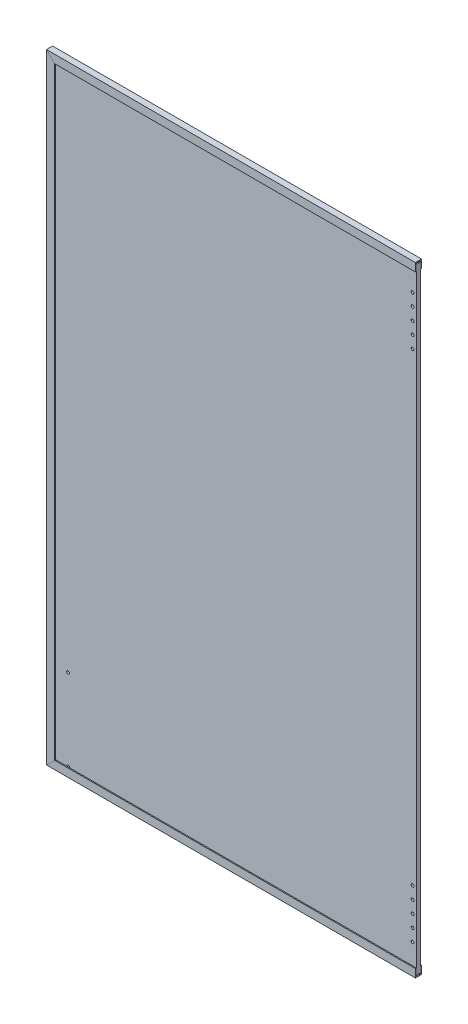
SolidWorks part; units mm, degrees
material "PC High Viscosity"
ref_plane "Front Plane" through (0, 0, 0) normal (0, 0, 1) x (1, 0, 0)
ref_plane "Top Plane" through (0, 0, 0) normal (0, 1, 0) x (1, 0, 0)
ref_plane "Right Plane" through (0, 0, 0) normal (1, 0, 0) x (0, 0, -1)
sketch "Shelf opening" plane through (0, 0, 0) normal (0, 0, 1) x (1, 0, 0)
  line L1 (0, 0) -> (577.85, 0)
  line L2 (0, 0) -> (0, 939.8)
  line L3 (0, 939.8) -> (577.85, 939.8)
  line L4 (577.85, 0) -> (577.85, 939.8)
  dimension "D1" = 577.85
  dimension "D2" = 939.8
sketch "Sketch2" plane through (0, 0, 0) normal (0, 0, 1) x (1, 0, 0)
  line L0 (577.85, 0) -> (577.85, 939.8) construction
  line L1 (3.175, 952.5) -> (577.85, 952.5)
  line L2 (3.175, 952.5) -> (3.175, -12.7)
  line L3 (3.175, -12.7) -> (577.85, -12.7)
  line L4 (577.85, 952.5) -> (577.85, -12.7)
  line L5 (0, 939.8) -> (577.85, 939.8) construction
  line L6 (0, 0) -> (0, 939.8) construction
  line L7 (0, 0) -> (577.85, 0) construction
  dimension "D1" = 12.7
  dimension "D2" = 3.175
  dimension "D3" = 12.7
extrude "Frame outer dimensions" add sketch "Sketch2" along normal mid plane 9.525
sketch "Sketch3" plane through (0, 0, 4.7625) normal (0, 0, 1) x (1, 0, 0)
  line L0 (577.85, -12.7) -> (577.85, 952.5) construction
  line L1 (577.85, 939.8) -> (15.875, 939.8)
  line L2 (577.85, 939.8) -> (577.85, 0)
  line L3 (577.85, 0) -> (15.875, 0)
  line L4 (15.875, 939.8) -> (15.875, 0)
  line L5 (577.85, 952.5) -> (3.175, 952.5) construction
  line L6 (3.175, 952.5) -> (3.175, -12.7) construction
  line L7 (3.175, -12.7) -> (577.85, -12.7) construction
  dimension "D1" = 12.7
  dimension "D2" = 12.7
  dimension "D3" = 12.7
extrude "Frame inner dimensions" cut sketch "Sketch3" against normal through all
sketch "Sketch4" plane through (0, 0, 0) normal (0, 0, 1) x (1, 0, 0)
  line L0 (577.85, 939.8) -> (577.85, 952.5) construction
  line L1 (577.85, 950.9125) -> (4.7625, 950.9125)
  line L2 (577.85, 950.9125) -> (577.85, -11.1125)
  line L3 (577.85, -11.1125) -> (4.7625, -11.1125)
  line L4 (4.7625, 950.9125) -> (4.7625, -11.1125)
  line L5 (577.85, 952.5) -> (3.175, 952.5) construction
  line L6 (3.175, 952.5) -> (3.175, -12.7) construction
  line L7 (3.175, -12.7) -> (577.85, -12.7) construction
  dimension "D1" = 1.5875
  dimension "D2" = 1.5875
  dimension "D3" = 1.5875
extrude "Frame profile" cut sketch "Sketch4" along normal offset from surface 1.5875 and the other way offset from surface (3.175 mm away) 1.5875 up to face at (293.6875, 469.9, 4.7625) other way up to face at (293.6875, 469.9, -4.7625)
sketch "Frame sections" plane through (0, 0, 4.7625) normal (0, 0, 1) x (1, 0, 0)
  line L0 (3.175, 952.5) -> (15.875, 939.8)
  line L1 (3.175, -12.7) -> (15.875, 0)
split "Frame section split" trim tools "Frame sections" bodies to split 103 resulting bodies 105 106 107
sketch "Sketch5" plane through (0, 0, 0) normal (0, 0, 1) x (1, 0, 0)
  line L0 (577.85, 939.8) -> (577.85, 952.5) construction
  line L1 (577.85, 949.325) -> (6.35, 949.325)
  line L2 (577.85, 949.325) -> (577.85, -9.525)
  line L3 (577.85, -9.525) -> (6.35, -9.525)
  line L4 (6.35, 949.325) -> (6.35, -9.525)
  line L5 (4.7625, 950.9125) -> (577.85, 950.9125) construction
  line L6 (4.7625, -11.1125) -> (4.7625, 950.9125) construction
  line L7 (577.85, -11.1125) -> (4.7625, -11.1125) construction
  dimension "D1" = 1.5875
  dimension "D2" = 1.5875
  dimension "D3" = 1.5875
  dimension "D4" = 571.5
  dimension "D5" = 958.85
extrude "Door panel" add sketch "Sketch5" along normal mid plane 5.588 separate body
sketch "Hinge positions" plane through (0, 0, 2.794) normal (0, 0, 1) x (1, 0, 0)
  line L0 (577.85, -9.525) -> (577.85, 949.325) construction
  line L1 (577.85, 917.575) -> (565.15, 917.575)
  line L2 (577.85, 917.575) -> (577.85, 822.325)
  line L3 (577.85, 822.325) -> (565.15, 822.325)
  line L4 (565.15, 917.575) -> (565.15, 822.325)
  line L5 (565.15, 117.475) -> (577.85, 117.475)
  line L6 (565.15, 117.475) -> (565.15, 22.225)
  line L7 (565.15, 22.225) -> (577.85, 22.225)
  line L8 (577.85, 117.475) -> (577.85, 22.225)
  line L10 (0, 0) -> (577.85, 0) construction
  line L11 (0, 939.8) -> (577.85, 939.8) construction
  dimension "D1" = 95.25
  dimension "D2" = 12.7
  dimension "D3" = 22.225
  dimension "D4" = 22.225
  dimension "D5" = 800.1
sketch "Sketch8" plane through (0, 0, 2.794) normal (0, 0, 1) x (1, 0, 0)
  line L0 (565.15, 69.85) -> (577.85, 69.85) construction
  line L2 (565.15, 117.475) -> (565.15, 22.225) construction
  line L3 (577.85, 117.475) -> (577.85, 22.225) construction
  line L4 (565.15, 869.95) -> (577.85, 869.95) construction
  line L6 (565.15, 917.575) -> (565.15, 822.325) construction
  line L7 (577.85, 917.575) -> (577.85, 822.325) construction
  point P0 (571.5, 31.75)
  point P11 (571.5, 50.8)
  point P12 (571.5, 69.85)
  point P13 (571.5, 88.9)
  point P14 (571.5, 107.95)
  point P15 (571.5, 850.9)
  point P16 (571.5, 869.95)
  point P17 (571.5, 889)
  point P18 (571.5, 908.05)
  point P19 (571.5, 831.85)
  dimension "D3" = 19.05
  dimension "D1" = 5
  dimension "D2" = 2
hole_wizard "#8 Clearance Hole1" positions "Sketch8" profile "Sketch9" hole size "#8" standard "ANSI Inch" end condition through all
sketch "Sketch9" plane through (571.5, 31.75, 2.794) normal (1, 0, 0) x (0, -1, 0)
  line L0 (0, 0) -> (0, 7.5565)
  line L1 (0, 7.5565) -> (2.2479, 7.5565)
  line L2 (2.2479, 7.5565) -> (2.2479, 0)
  line L5 (2.2479, 0) -> (0, 0)
  line L11 (0, -6.35) -> (0, 107.95) construction
  dimension "Thru Hole Dia." = 4.4958
  dimension "Thru Hole Depth" = 7.5565
sketch "Handle position" plane through (0, 0, 2.794) normal (0, 0, 1) x (1, 0, 0)
  line L0 (6.35, 949.325) -> (6.35, -9.525) construction
  line L1 (6.35, 139.7) -> (44.45, 139.7)
  line L2 (6.35, 139.7) -> (6.35, -9.525)
  line L3 (6.35, -9.525) -> (44.45, -9.525)
  line L4 (44.45, 139.7) -> (44.45, -9.525)
  line L5 (6.35, -9.525) -> (577.85, -9.525) construction
  dimension "D1" = 149.225
  dimension "D2" = 38.1
sketch "Sketch11" plane through (0, 0, 2.794) normal (0, 0, 1) x (1, 0, 0)
  line L0 (34.925, 127) -> (34.925, 0) construction
  line L2 (6.35, 139.7) -> (6.35, -9.525) construction
  line L3 (6.35, -9.525) -> (44.45, -9.525) construction
  point P0 (34.925, 0)
  point P2 (34.925, 127)
  dimension "D1" = 28.575
  dimension "D2" = 9.525
  dimension "D3" = 136.525
hole_wizard "#8 Clearance Hole2" positions "Sketch11" profile "Sketch12" hole size "#8" standard "ANSI Inch" end condition through all
sketch "Sketch12" plane through (34.925, 0, 2.794) normal (1, 0, 0) x (0, -1, 0)
  line L0 (0, 0) -> (0, 7.5565)
  line L1 (0, 7.5565) -> (2.2479, 7.5565)
  line L2 (2.2479, 7.5565) -> (2.2479, 0)
  line L5 (2.2479, 0) -> (0, 0)
  line L11 (0, -6.35) -> (0, 107.95) construction
  dimension "Thru Hole Dia." = 4.4958
  dimension "Thru Hole Depth" = 7.5565
mirror "Mirror1" about plane through (0, 0, 0) normal (1, 0, 0) of bodies 105 106 107 113 108
delete or keep bodies "Body-Delete/Keep 1" type keep bodies bodies 105 106 107 113
delete or keep bodies "Body-Delete/Keep 2" [suppressed] type keep bodies bodies 109 110 111 112
